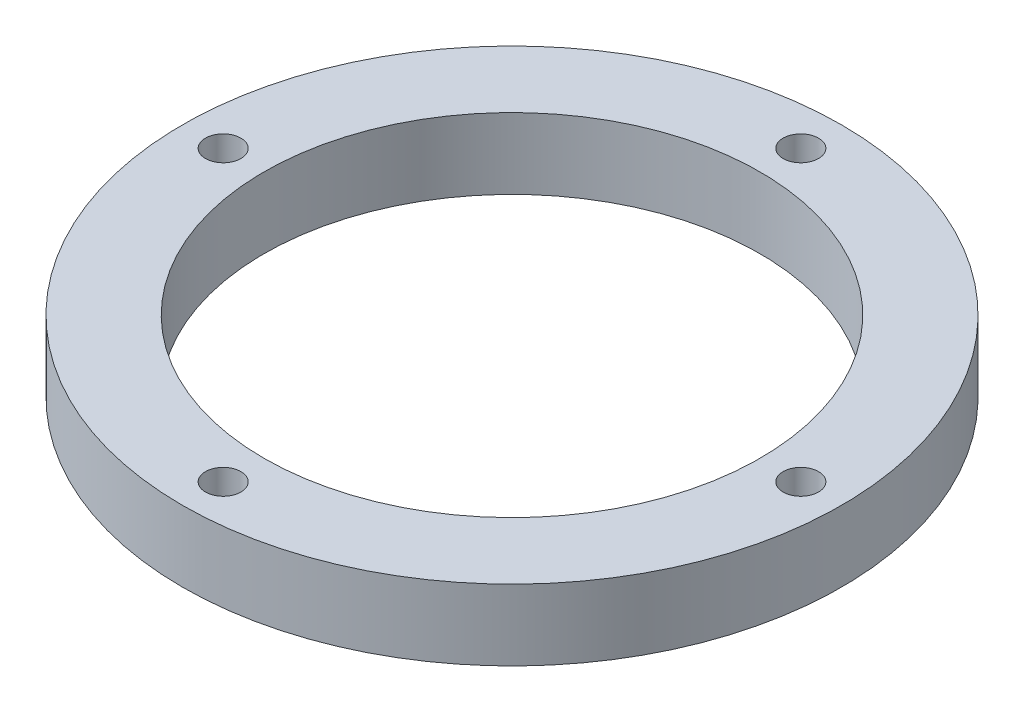
SolidWorks part; units mm, degrees
material "1060 Alloy"
ref_plane "Frontal Plane" through (0, 0, 0) normal (0, 0, 1) x (1, 0, 0)
ref_plane "Horizontal Plane" through (0, 0, 0) normal (0, 1, 0) x (1, 0, 0)
ref_plane "Profile Plane" through (0, 0, 0) normal (1, 0, 0) x (0, 0, -1)
sketch "Sketch1" plane through (0, 0, 0) normal (0, 1, 0) x (1, 0, 0)
  circle A0 centre (0, 0) radius 35
  circle A1 centre (0, 0) radius 46.5
  circle A2 centre (-40.75, 0) radius 2.5
  circle A6 centre (0, 40.75) radius 2.5
  circle A7 centre (40.75, 0) radius 2.5
  circle A8 centre (0, -40.75) radius 2.5
  point P15 (0, 0)
  dimension "D1" = 70
  dimension "D3" = 5
  dimension "D2" = 11.5
  dimension "D4" = 40.75
  dimension "D5" = 4
extrude "Boss-Extrude1" add sketch "Sketch1" along normal blind 10
equation "\"D1@Sketch1\"=\"TurntableID\""
equation "\"D2@Sketch1\"=(\"TurntableOD\"-\"TurntableID\")*.25 - 1mm"
equation "\"D4@Sketch1\"=\"TurntableInnerHoleRadius\""
equation "\"PinDiameter\"= 0"
equation "\"WallThickness\"= 0.5cm"
equation "\"BottomPlateX\"= 3ft"
equation "\"BottomPlateZ\"= 2ft"
equation "\"BottomPlateHoleD\"=((\"ArmPlateX\")^2+(\"ArmPlateDepth\")^2)^.5+ 10mm"
equation "\"ActuatorL\"= 35cm"
equation "\"ActuatorPinD\"= 6.35mm"
equation "\"ActuatorPinL\"= 15cm"
equation "\"Box-X\"= 40cm"
equation "\"Box-Z\"= 20cm"
equation "\"Box-Y\"= 30cm"
equation "\"ArmPlateThickness\"= .125in"
equation "\"ArmPlateX\"= 18in"
equation "\"ArmPlateDepth\"= 7.1875in"
equation "\"Arm1X\"= 5cm"
equation "\"Arm1L\"= 60cm"
equation "\"Arm2GAP\"= 5cm"
equation "\"Arm2L\"= 60cm"
equation "\"Arm2H\"= 5cm"
equation "\"Arm2Extension\"= 5cm"
equation "\"Arm3GAP\"= 5cm"
equation "\"Arm3L\"= 60cm"
equation "\"Arm3H\"= 5cm"
equation "\"Pin1-2L\"= \"Arm2GAP\" + (2 * \"WallThickness\")"
equation "\"Pin2-3L\"= \"Arm3GAP\" + (4 * \"WallThickness\")"
equation "\"DCMotor1D\"= 65mm"
equation "\"DCMotor1L\"= 215mm"
equation "\"DCMotor1ShaftL\"= 30mm"
equation "\"DCMotor2X\"= 68mm"
equation "\"DCMotor2D\"= 65mm"
equation "\"DCMotor2L\"= 208mm"
equation "\"DCMotor2ShaftL\"= 39mm"
equation "\"DCMotor2ShaftD\"= 15mm"
equation "\"BenchDepth\"= 5cm"
equation "\"BenchH\"= 10cm"
equation "\"BenchL\"= 15cm"
equation "\"PillowBlockW\"= 5cm"
equation "\"PillowBlockCenterH\"= \"DCMotor2X\"/2"
equation "\"EncoderRadius\"= 19mm"
equation "\"EncoderShaftL\"= 15mm"
equation "\"EncoderL\"= 33mm"
equation "\"EncoderHousingThickness\"= 7.5mm"
equation "\"TurntableID\"= 70mm"
equation "\"TurntableInner2*t\" = (\"TurntableOD\"-\"TurntableID\")*.25 - 1mm"
equation "\"TurntableOD\"= 120mm"
equation "\"TurntableInnerHoleRadius\"= \"TurntableID\"*.5 + \"TurntableInner2*t\"*.5"
equation "\"TurntableInner2*t\" = (\"TurntableOD\"-\"TurntableID\")*.25 - .5mm"
equation "\"BottomPlateZ\"= 60cm"
equation "\"TurntableInnerHoleRadius\"= \"TurntableID\"*.5 + \"Turntable2*t\""
equation "\"DCMotor2ShaftD\"= 14mm"
equation "\"DCMotor2ShaftL\"= 34mm"
equation "\"DCMotor2L\"= 153mm"
equation "\"DCMotor2D\"= 57mm"
equation "\"DCMotor2X\"= 57mm"
equation "\"DCMotor1ShaftL\"= \"ArmPlateThickness\" + 1.7cm"
equation "\"DCMotor1L\"= 20cm"
equation "\"ArmPlateDepth\"= 20cm"
equation "\"ArmPlateX\"= 40cm"
equation "\"ArmPlateThickness\"= 1cm"
equation "\"ActuatorPinL\"= 13cm"
equation "\"ActuatorPinD\"= 6mm"
equation "\"BottomPlateX\"= 100cm"
equation "\"PinDiameter\"= 1cm"
